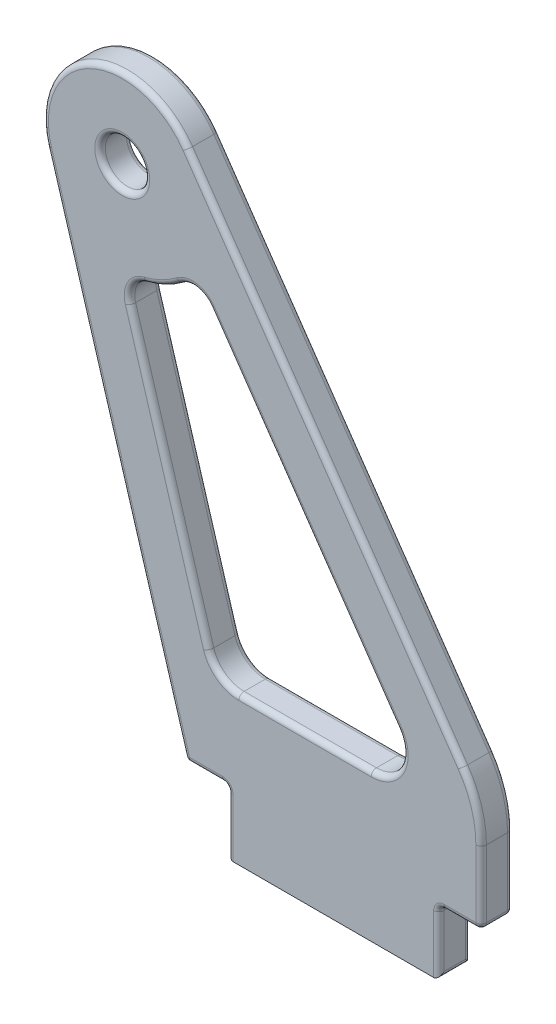
SolidWorks part; units mm, degrees
ref_plane "Front Plane" through (0, 0, 0) normal (0, 0, 1) x (1, 0, 0)
ref_plane "Top Plane" through (0, 0, 0) normal (0, 1, 0) x (1, 0, 0)
ref_plane "Right Plane" through (0, 0, 0) normal (1, 0, 0) x (0, 0, -1)
sketch "Sketch1" plane through (0, 0, 0) normal (0, 0, 1) x (1, 0, 0)
  line L0 (-10, 0) -> (10, 0)
  line L1 (-10, 0) -> (-10, 6)
  line L2 (-10, 6) -> (-14, 6)
  line L3 (-14, 6) -> (-27.1823, 49.8403)
  line L4 (10, 0) -> (10, 6)
  line L5 (10, 6) -> (14, 6)
  line L6 (14, 6) -> (14, 16)
  line L7 (14, 16) -> (-13.8303, 56.2644)
  circle A0 centre (-20, 52) radius 2.1
  arc A1 (-13.8303, 56.2644) -> (-27.1823, 49.8403) centre (-20, 52) ccw
  dimension "D1" = 4.2
  dimension "D2" = 15
  dimension "D3" = 52
  dimension "D4" = 20
  dimension "D5" = 6
  dimension "D6" = 4
  dimension "D7" = 6
  dimension "D8" = 4
  dimension "D9" = 10
  dimension "D10" = 20
extrude "Boss-Extrude1" add sketch "Sketch1" along normal blind 3
sketch "Sketch2" plane through (0, 0, 3) normal (0, 0, 1) x (1, 0, 0)
  line L8 (-8.9538, 14) -> (3.5838, 14)
  line L9 (10, 6) -> (14, 6) construction
  line L16 (-22.3941, 51.2801) -> (-10.2823, 11)
  line L17 (-10.2823, 11) -> (-5, 11)
  line L18 (-5, 11) -> (-5, 5)
  line L19 (-5, 5) -> (5, 5)
  line L20 (5, 5) -> (5, 11)
  line L21 (5, 11) -> (9, 11)
  line L22 (9, 11) -> (9, 14.4402)
  line L23 (9, 14.4402) -> (-17.9434, 53.4215)
  line L24 (-19.2299, 40.7569) -> (-11.8267, 16.1361)
  line L31 (6.0517, 18.7058) -> (-11.6954, 44.382)
  arc A1 (-17.8029, 43.2723) -> (-14.5515, 44.8367) centre (-20, 52) ccw
  arc A2 (-17.9434, 53.4215) -> (-22.3941, 51.2801) centre (-20, 52) ccw
  arc A3 (-11.6954, 44.382) -> (-14.5515, 44.8367) centre (-13.3407, 43.2448) ccw
  arc A4 (-19.2299, 40.7569) -> (-17.8029, 43.2723) centre (-17.3146, 41.3328) cw
  arc A5 (-11.8267, 16.1361) -> (-8.9538, 14) centre (-8.9538, 17) ccw
  arc A6 (6.0517, 18.7058) -> (3.5838, 14) centre (3.5838, 17) cw
  dimension "D2" = 18
  dimension "D3" = 2
  dimension "D4" = 3
  dimension "D5" = 8
  dimension "D1" = 5
extrude "Cut-Extrude1" cut sketch "Sketch2" against normal blind 30.5
fillet "Fillet1" radius 10 1 edges at (14, 16, 1.5)
fillet "Fillet2" radius 0.5 42 edges at (-16.098, 43.8899, 0) (-13.0262, 45.2199, 0) (-2.8219, 31.5439, 0) (6.2406, 15.6067, 0) (-2.685, 14, 0) (-10.7438, 14.5926, 0) (-15.5283, 28.4465, 0) (-16.098, 43.8899, 3) (-13.0262, 45.2199, 3) (-2.8219, 31.5439, 3) (6.2406, 15.6067, 3) (-2.685, 14, 3) (-10.7438, 14.5926, 3) (-15.5283, 28.4465, 3) (14, 9.4402, 0) (13.5463, 15.8585, 0) (-20.5912, 27.9202, 0) (-23.2517, 58.7584, 0) (14, 9.4402, 3) (13.5463, 15.8585, 3) (-20.5912, 27.9202, 3) (-23.2517, 58.7584, 3) (12, 6, 3) (14, 6, 1.5) (12, 6, 0) (-14, 6, 1.5) (-12, 6, 3) (-12, 6, 0) (-10, 6, 1.5) (-10, 3, 3) (-10, 0, 1.5) (-10, 3, 0) (10, 0, 1.5) (10, 3, 3) (10, 6, 1.5) (10, 3, 0) (-19.0542, 42.3197, 0) (-19.0542, 42.3197, 3) (-17.9, 52, 0) (-17.9, 52, 3) (-0.8021, 37.4153, 0) (-0.8021, 37.4153, 3)
